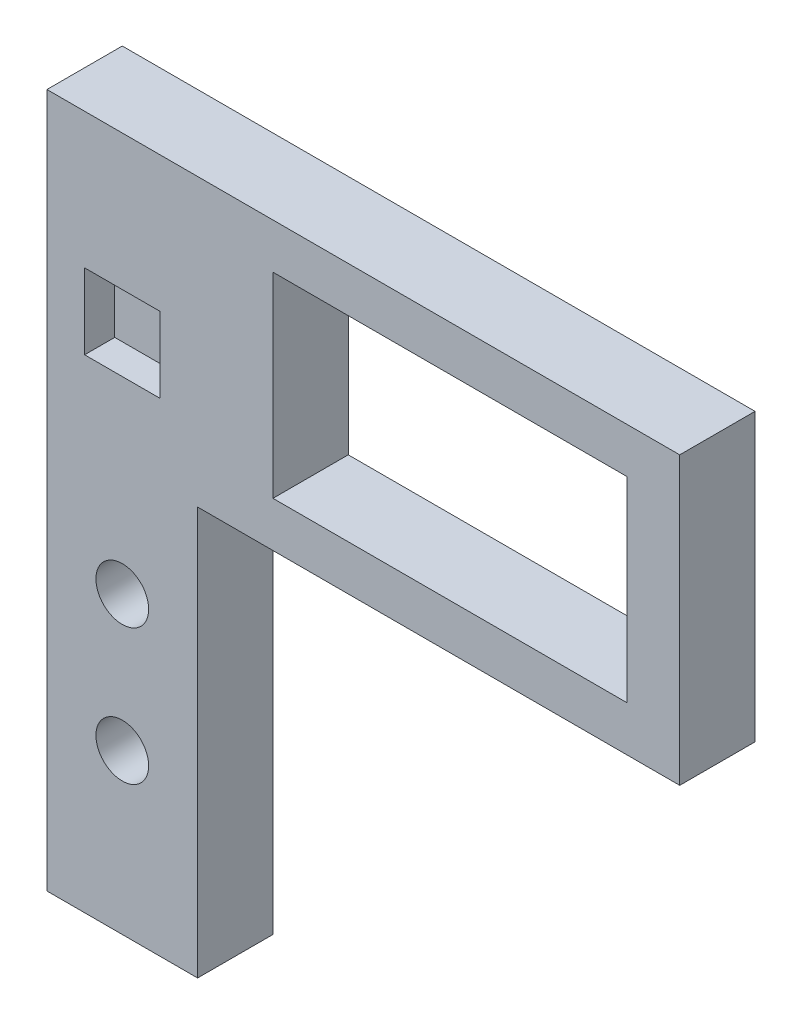
SolidWorks part; units mm, degrees
ref_plane "Ebene vorne" through (0, 0, 0) normal (0, 0, 1) x (1, 0, 0)
ref_plane "Ebene oben" through (0, 0, 0) normal (0, 1, 0) x (1, 0, 0)
ref_plane "Ebene rechts" through (0, 0, 0) normal (1, 0, 0) x (0, 0, -1)
sketch "Skizze1" plane through (0, 0, 0) normal (0, 0, 1) x (1, 0, 0)
  line L5 (5, 33.9257) -> (-5, 33.9257)
  line L6 (5, 33.9257) -> (5, -12.1472)
  line L8 (5, 30.6757) -> (5, 18.1757)
  line L11 (5, 30.9257) -> (10, 30.9257)
  line L12 (5, 30.9257) -> (5, 17.9257)
  line L19 (5, 33.9257) -> (37, 33.9257)
  line L20 (5, 33.9257) -> (5, 30.9257)
  line L21 (5, 30.9257) -> (37, 30.9257)
  line L22 (37, 33.9257) -> (37, 30.9257)
  line L23 (5, 33.9257) -> (37, 30.9257) construction
  line L24 (5, 30.9257) -> (37, 33.9257) construction
  line L25 (5, -12.1472) -> (-5, -12.1472)
  line L26 (-5, 33.9257) -> (-5, -12.1472)
  line L27 (5, 33.9257) -> (-5, -12.1472) construction
  line L28 (5, -12.1472) -> (-5, 33.9257) construction
  line L31 (37, 17.9257) -> (5, 17.9257)
  line L32 (37, 17.9257) -> (37, 14.9257)
  line L33 (5, 17.9257) -> (10, 17.9257)
  line L34 (10, 30.9257) -> (10, 17.9257)
  line L35 (5, 30.9257) -> (10, 17.9257) construction
  line L36 (5, 17.9257) -> (10, 30.9257) construction
  line L37 (37, 30.9257) -> (33.5, 30.9257)
  line L38 (37, 30.9257) -> (37, 17.9257)
  line L39 (37, 17.9257) -> (33.5, 17.9257)
  line L40 (33.5, 30.9257) -> (33.5, 17.9257)
  line L41 (37, 30.9257) -> (33.5, 17.9257) construction
  line L42 (37, 17.9257) -> (33.5, 30.9257) construction
  line L43 (37, 14.9257) -> (5, 14.9257)
  line L44 (5, 17.9257) -> (5, 14.9257)
  line L45 (37, 17.9257) -> (5, 14.9257) construction
  line L46 (37, 14.9257) -> (5, 17.9257) construction
  circle A0 centre (0, 7.4257) radius 1.75
  circle A1 centre (0, -1.5743) radius 1.75
  point P3 (0, 10.8893)
  point P4 (0, 7.4257)
  point P14 (22.5664, 24.4257)
  point P19 (21, 16.4257)
  point P24 (21, 32.4257)
  point P29 (21.8632, 16.4257)
  point P30 (7.5, 24.4257)
  point P32 (35.25, 24.4257)
  dimension "D4" = 3.5
  dimension "D5" = 3.5
  dimension "D1" = 0
  dimension "D2" = 10
  dimension "D3" = 3
  dimension "D6" = 9
  dimension "D7" = 17
  dimension "D8" = 32
  dimension "D10" = 3
  dimension "D11" = 3.4635
  dimension "D13" = 6.5
  dimension "D14" = 5
  dimension "D16" = 23.5
extrude "Aufsatz-Linear austragen1" add sketch "Skizze1" along normal blind 5 contours L5 L26 L25 L6 A1 A0 | L34 L11 L6 L31 | L43 L32 L31 L6 | L22 L19 L6 L11 L21 | L21 L40 L31 L38
sketch "Skizze2" plane through (0, 0, 5) normal (0, 0, -1) x (-1, 0, 0)
  line L1 (2.5, 24.9257) -> (-2.5, 24.9257)
  line L2 (2.5, 24.9257) -> (2.5, 19.9257)
  line L3 (2.5, 19.9257) -> (-2.5, 19.9257)
  line L4 (-2.5, 24.9257) -> (-2.5, 19.9257)
  line L5 (2.5, 24.9257) -> (-2.5, 19.9257) construction
  line L6 (2.5, 19.9257) -> (-2.5, 24.9257) construction
  circle A2 centre (0, 7.4257) radius 1.75 construction
  point P4 (0, 22.4257)
  dimension "D1" = 5
  dimension "D2" = 5
  dimension "D3" = 15
extrude "Schnitt-Linear austragen2" cut sketch "Skizze2" along normal blind 2
